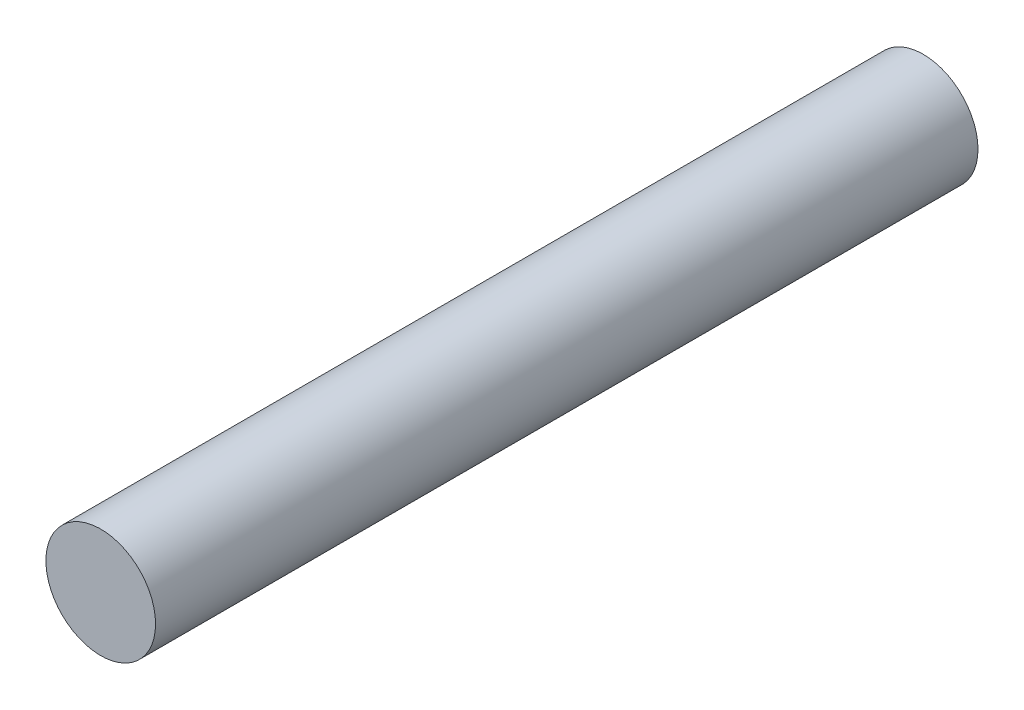
SolidWorks part; units mm, degrees
ref_plane "Front Plane" through (0, 0, 0) normal (0, 0, 1) x (1, 0, 0)
ref_plane "Top Plane" through (0, 0, 0) normal (0, 1, 0) x (1, 0, 0)
ref_plane "Right Plane" through (0, 0, 0) normal (1, 0, 0) x (0, 0, -1)
sketch "Sketch1" plane through (0, 0, 0) normal (0, 0, 1) x (1, 0, 0)
  circle A0 centre (0, 0) radius 2
extrude "Boss-Extrude3" add sketch "Sketch1" along normal blind 30
